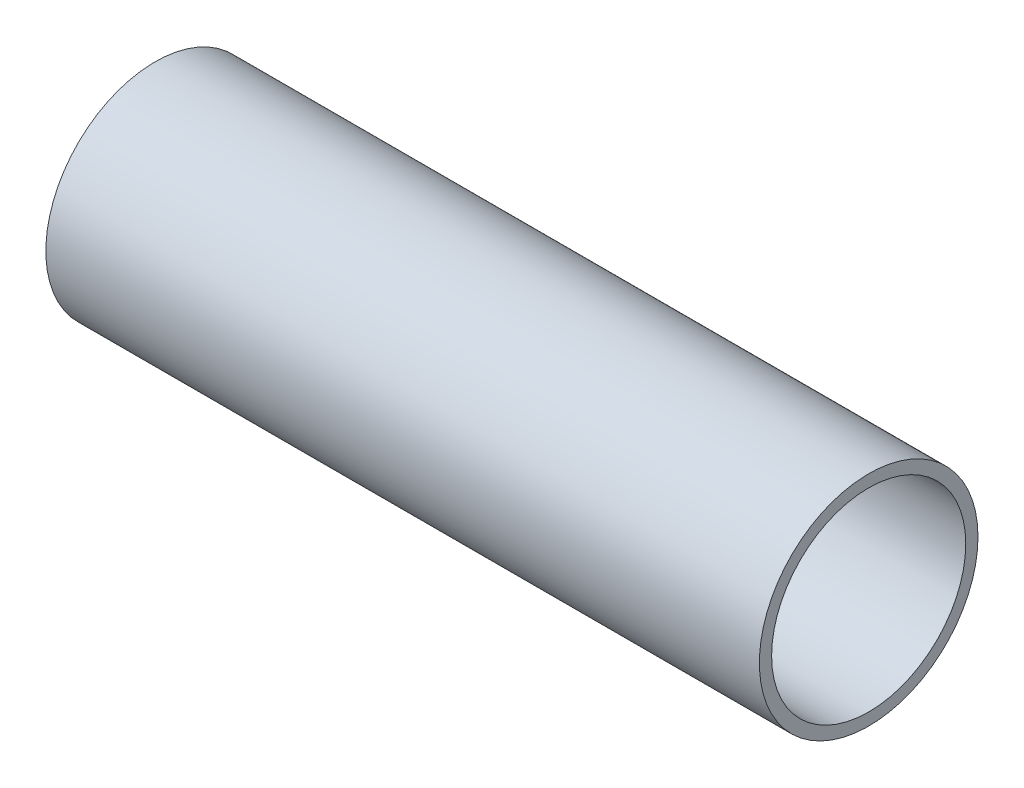
SolidWorks part; units mm, degrees
ref_plane "Front Plane" through (0, 0, 0) normal (0, 0, 1) x (1, 0, 0)
ref_plane "Top Plane" through (0, 0, 0) normal (0, 1, 0) x (1, 0, 0)
ref_plane "Right Plane" through (0, 0, 0) normal (1, 0, 0) x (0, 0, -1)
sketch "Sketch1" plane through (0, 0, 0) normal (1, 0, 0) x (0, 0, -1)
  circle A0 centre (0, 0) radius 6.35
  circle A1 centre (0, 0) radius 5.6388
  dimension "D1" = 12.7
  dimension "D2" = 11.2776
extrude "Boss-Extrude1" add sketch "Sketch1" along normal up to surface (41.4473 mm away) from surface
